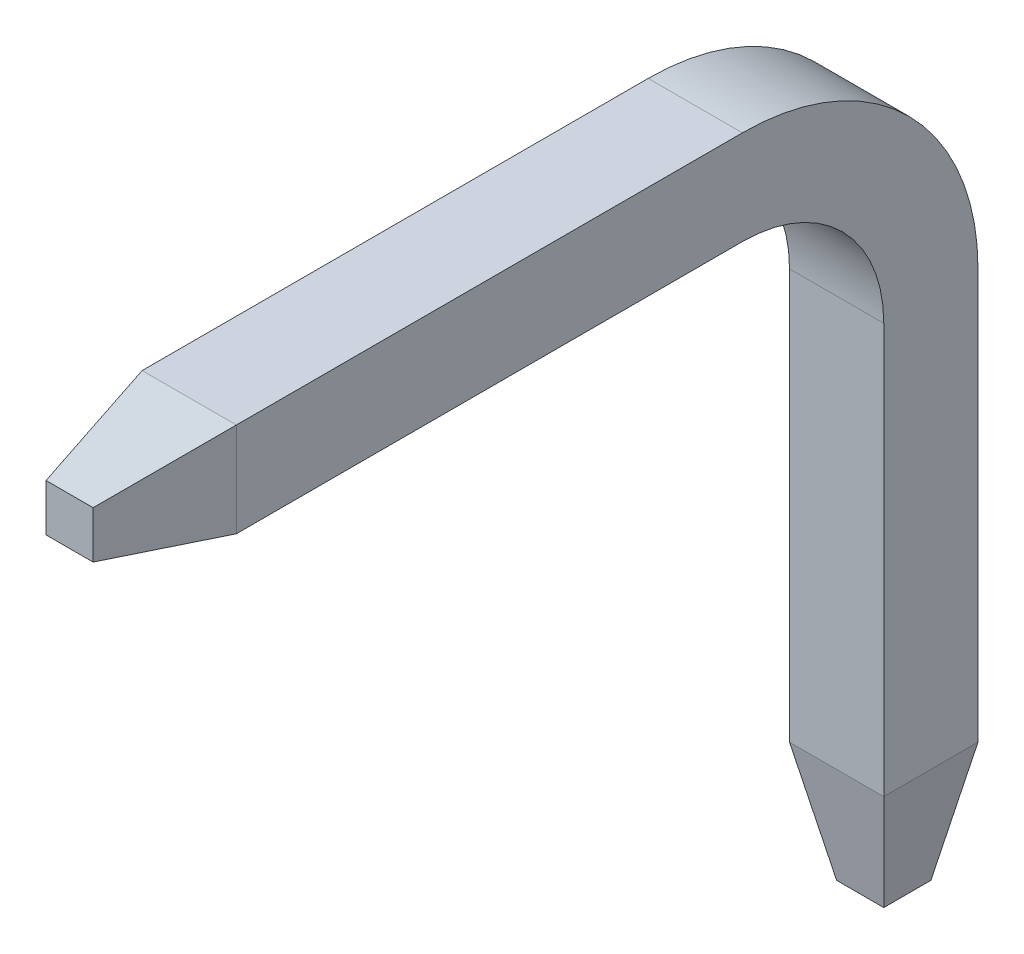
SolidWorks part; units mm, degrees
ref_plane "Front Plane" through (0, 0, 0) normal (0, 0, 1) x (1, 0, 0)
ref_plane "Top Plane" through (0, 0, 0) normal (0, 1, 0) x (1, 0, 0)
ref_plane "Right Plane" through (0, 0, 0) normal (1, 0, 0) x (0, 0, -1)
sketch "Sketch1" plane through (0, 0, 0) normal (1, 0, 0) x (0, 0, -1)
  line L0 (-2, 0) -> (-8.64, 0) construction
  line L1 (0, -2) -> (0, -7.62) construction
  line L8 (0.5, -2) -> (0.5, -7.62)
  line L9 (-2, 0.5) -> (-8.64, 0.5)
  line L10 (-0.5, -2) -> (-0.5, -7.62)
  line L11 (-2, -0.5) -> (-8.64, -0.5)
  line L12 (0.5, -7.62) -> (-0.5, -7.62)
  line L13 (-8.64, 0.5) -> (-8.64, -0.5)
  arc A2 (-2, 0) -> (0, -2) centre (-2, -2) cw construction
  arc A3 (-2, 0.5) -> (0.5, -2) centre (-2, -2) cw
  arc A4 (-2, -0.5) -> (-0.5, -2) centre (-2, -2) cw
  dimension "D3" = 2
  dimension "D1" = 8.64
  dimension "D2" = 7.62
  dimension "D4" = 0.5
  dimension "D5" = 0.5
extrude "Boss-Extrude1" add sketch "Sketch1" along normal mid plane 1
chamfer "Chamfer1" distance 1.27 distance2 0.25 4 edges at (-0.5, 0, 8.64) (0, -0.5, 8.64) (0.5, 0, 8.64) (0, 0.5, 8.64)
chamfer "Chamfer2" distance 0.25 distance2 1.27 4 edges at (-0.5, -7.62, 0) (0, -7.62, 0.5) (0.5, -7.62, 0) (0, -7.62, -0.5)
